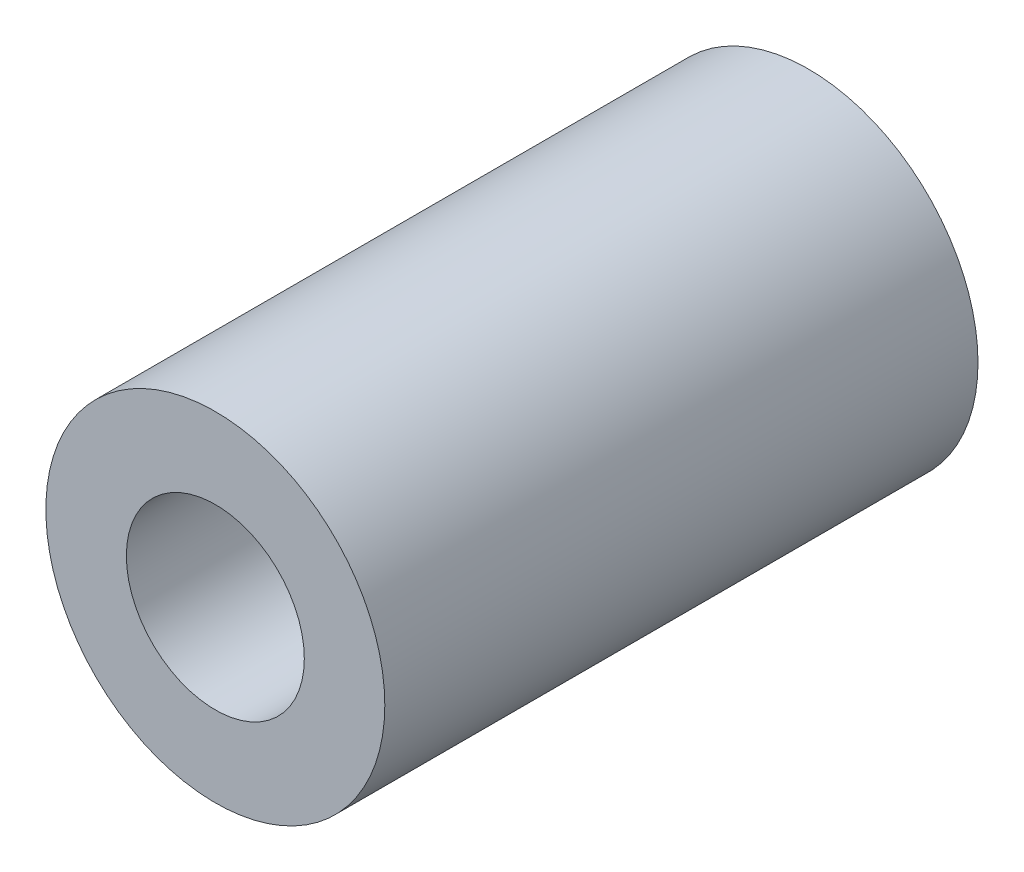
SolidWorks part; units mm, degrees
ref_plane "Front Plane" through (0, 0, 0) normal (0, 0, 1) x (1, 0, 0)
ref_plane "Top Plane" through (0, 0, 0) normal (0, 1, 0) x (1, 0, 0)
ref_plane "Right Plane" through (0, 0, 0) normal (1, 0, 0) x (0, 0, -1)
sketch "Sketch1" plane through (0, 0, 0) normal (0, 0, 1) x (1, 0, 0)
  circle A0 centre (0, 0) radius 4
  circle A1 centre (0, 0) radius 2.1
  dimension "OD" = 8
  dimension "ID" = 4.2
extrude "Extrude1" add sketch "Sketch1" along normal mid plane 14
sketch "Sketch2" plane through (0, 0, 0) normal (1, 0, 0) x (0, 0, -1)
  line L0 (-7, -2.1) -> (7, -2.1) construction
  line L3 (7, 2.1) -> (-7, 2.1) construction
  line L5 (-7, -2.1) -> (7, -2.1)
  line L6 (7, 2.1) -> (-7, 2.1)
sketch "Sketch4" plane through (0, 0, 7) normal (0, 0, 1) x (1, 0, 0)
  line L0 (0, 0) -> (-1.4849, 1.4849)
  line L1 (0, -4.4) -> (0, 4.4) construction
  circle A0 centre (0, 0) radius 2.1 construction
  dimension "D1" = 45
